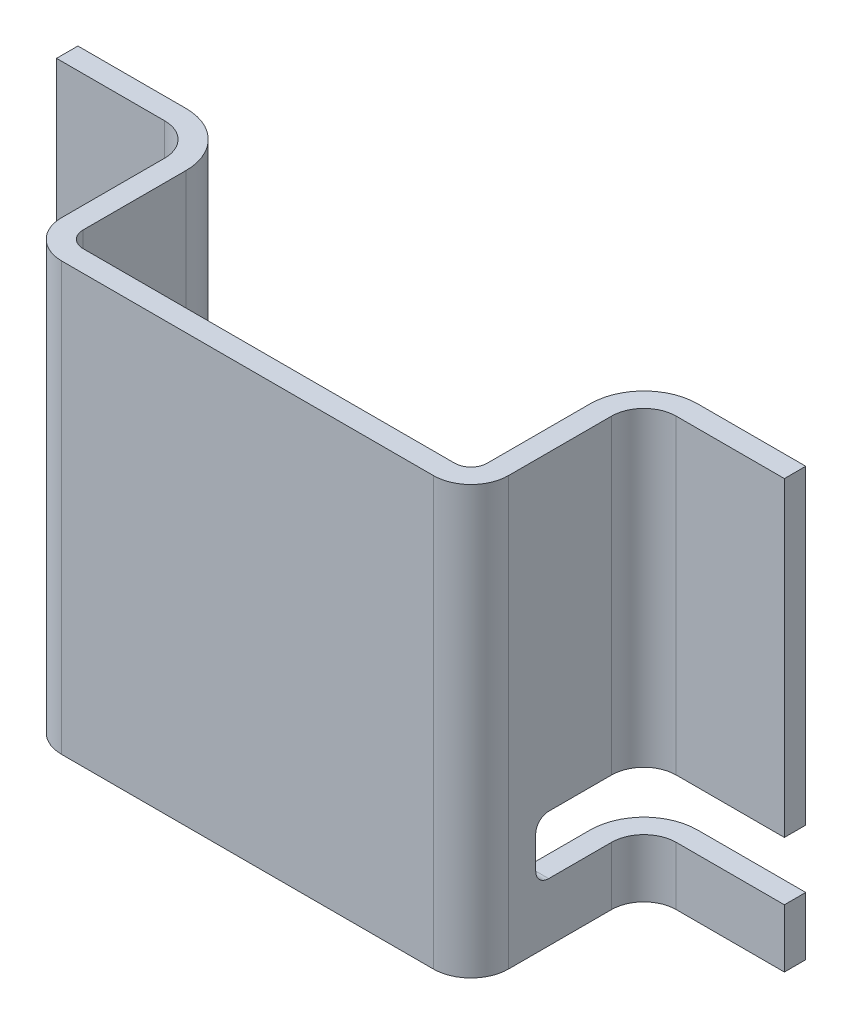
SolidWorks part; units mm, degrees
material "Кованая медь"
ref_plane "Front" through (0, 0, 0) normal (0, 0, 1) x (1, 0, 0)
ref_plane "Top" through (0, 0, 0) normal (0, 1, 0) x (1, 0, 0)
ref_plane "Right" through (0, 0, 0) normal (1, 0, 0) x (0, 0, -1)
sketch "Эскиз1" plane through (0, 0, 0) normal (0, 1, 0) x (1, 0, 0)
  line L0 (-5.62, 0) -> (-3.95, 0)
  line L1 (-3.12, -0.83) -> (-3.12, -2.42)
  line L2 (-2.87, -2.67) -> (2.87, -2.67)
  line L3 (3.12, -2.42) -> (3.12, -0.83)
  line L4 (3.95, 0) -> (5.62, 0)
  line L5 (5.62, 0) -> (5.62, -0.33)
  line L6 (5.62, -0.33) -> (3.95, -0.33)
  line L7 (3.45, -0.83) -> (3.45, -2.42)
  line L8 (2.87, -3) -> (-2.87, -3)
  line L9 (-3.45, -2.42) -> (-3.45, -0.83)
  line L10 (-3.95, -0.33) -> (-5.62, -0.33)
  line L11 (-5.62, -0.33) -> (-5.62, 0)
  line L12 (0, -3) -> (0, -2.67) construction
  line L13 (0, -2.67) -> (0, 0) construction
  arc A0 (-3.95, 0) -> (-3.12, -0.83) centre (-3.95, -0.83) cw
  arc A1 (-3.12, -2.42) -> (-2.87, -2.67) centre (-2.87, -2.42) ccw
  arc A2 (2.87, -2.67) -> (3.12, -2.42) centre (2.87, -2.42) ccw
  arc A3 (3.12, -0.83) -> (3.95, 0) centre (3.95, -0.83) cw
  arc A4 (3.95, -0.33) -> (3.45, -0.83) centre (3.95, -0.83) ccw
  arc A5 (3.45, -2.42) -> (2.87, -3) centre (2.87, -2.42) cw
  arc A6 (-2.87, -3) -> (-3.45, -2.42) centre (-2.87, -2.42) cw
  arc A7 (-3.45, -0.83) -> (-3.95, -0.33) centre (-3.95, -0.83) ccw
  point P32 (0, 0)
  point P34 (0, 0)
  point P35 (1.8385, -1.3519)
  point P36 (1.6535, -0.5934)
  point P37 (1.6885, -0.8004)
  point P38 (1.8882, -0.301)
  point P39 (-1.2698, -0.4844)
  point P40 (-0.7295, -1.32)
  point P41 (-1.2329, -0.8844)
  point P42 (-1.2206, -0.913)
  point P43 (-0.95, -0.5017)
  point P44 (0, 0)
  point P45 (-1.1707, -0.8961)
  point P46 (-0.95, -0.3535)
  point P47 (-1.5819, -0.33)
  point P48 (-0.95, -0.6083)
  point P49 (0.75, -1.3009)
  point P50 (0.75, -1.491)
  dimension "D1" = 0.33
  dimension "D4" = 0.25
  dimension "D5" = 0.5
  dimension "D2" = 6.9
  dimension "D3" = 2.5
  dimension "D6" = 3
extrude "Бобышка-Вытянуть1" add sketch "Эскиз1" along normal mid plane 6.6
sketch "Эскиз2" plane through (0, 0, 0) normal (1, 0, 0) x (0, 0, -1)
  line L0 (0, -1.5) -> (0, -2.4)
  line L1 (0, -2.4) -> (-1.8, -2.4)
  line L2 (-2, -2.2) -> (-2, -1.7)
  line L3 (-1.8, -1.5) -> (0, -1.5)
  arc A0 (-1.8, -2.4) -> (-2, -2.2) centre (-1.8, -2.2) cw
  arc A1 (-2, -1.7) -> (-1.8, -1.5) centre (-1.8, -1.7) cw
  dimension "D1" = 4.8
  dimension "D4" = 0.2
  dimension "D2" = 0.9
  dimension "D3" = 2
extrude "Вырез-Вытянуть1" cut sketch "Эскиз2" against normal through all both and the other way through all
